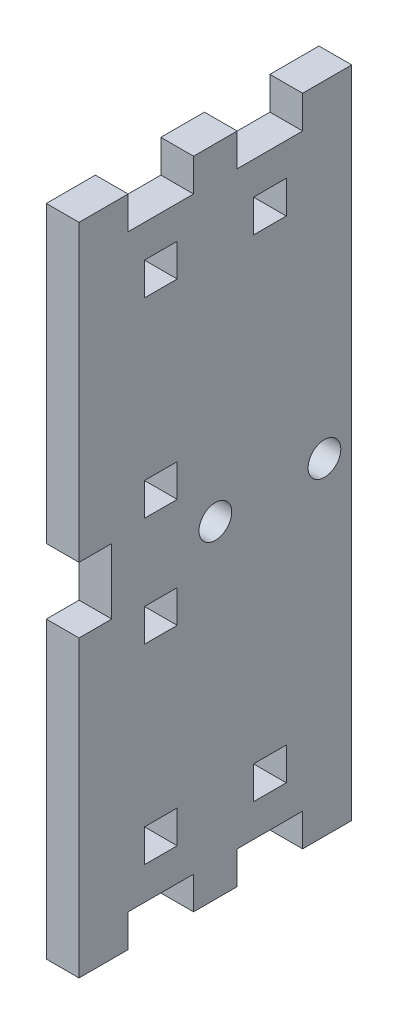
SolidWorks part; units mm, degrees
ref_plane "Front Plane" through (0, 0, 0) normal (0, 0, 1) x (1, 0, 0)
ref_plane "Top Plane" through (0, 0, 0) normal (0, 1, 0) x (1, 0, 0)
ref_plane "Right Plane" through (0, 0, 0) normal (1, 0, 0) x (0, 0, -1)
sketch "Sketch1" plane through (0, 0, 0) normal (1, 0, 0) x (0, 0, -1)
  line L0 (8, 30) -> (12.5, 30)
  line L1 (-12.5, 30) -> (-8, 30)
  line L2 (-12.5, 30) -> (-12.5, -30)
  line L3 (-12.5, -30) -> (-8, -30)
  line L4 (12.5, 30) -> (12.5, -30)
  line L7 (-8, 30) -> (-8, 27)
  line L8 (-2, 30) -> (-2, 27)
  line L9 (-8, 27) -> (-2, 27)
  line L10 (-2, -30) -> (2, -30)
  line L11 (2, 30) -> (2, 27)
  line L12 (8, 30) -> (8, 27)
  line L13 (2, 27) -> (8, 27)
  line L14 (-2, 30) -> (2, 30)
  line L16 (-8, -30) -> (-8, -27)
  line L17 (2, -27) -> (8, -27)
  line L18 (8, -27) -> (8, -30)
  line L19 (2, -30) -> (2, -27)
  line L20 (-8, -27) -> (-2, -27)
  line L21 (-2, -30) -> (-2, -27)
  line L22 (8, -30) -> (12.5, -30)
  point P0 (0, 0)
  point P6 (5, 27)
  point P15 (-5, 27)
  dimension "D1" = 25
  dimension "D2" = 60
  dimension "D3" = 6
  dimension "D4" = 6
  dimension "D5" = 3
  dimension "D6" = 3
  dimension "D7" = 7.5
  dimension "D8" = 7.5
extrude "Boss-Extrude1" add sketch "Sketch1" along normal blind 3
sketch "Sketch2" plane through (3, 0, 0) normal (1, 0, 0) x (0, 0, -1)
  line L0 (-18.5174, 0) -> (21.8209, 0) construction
  line L1 (-21.3613, 24) -> (23.7629, 24) construction
  line L2 (-2, 27) -> (-8, 27) construction
  line L3 (-6.5, 24) -> (-3.5, 24)
  line L4 (-6.5, 24) -> (-6.5, 21)
  line L5 (-3.5, 24) -> (-3.5, 21)
  line L6 (-6.5, 21) -> (-3.5, 21)
  line L7 (3.5, 24) -> (6.5, 24)
  line L8 (3.5, 24) -> (3.5, 21)
  line L9 (6.5, 24) -> (6.5, 21)
  line L10 (3.5, 21) -> (6.5, 21)
  line L11 (-12.5, 30) -> (-12.5, -30) construction
  line L12 (12.5, -30) -> (12.5, 30) construction
  line L13 (3.5, -21) -> (6.5, -21)
  line L14 (6.5, -24) -> (6.5, -21)
  line L15 (3.5, -24) -> (3.5, -21)
  line L16 (3.5, -24) -> (6.5, -24)
  line L17 (-6.5, -21) -> (-3.5, -21)
  line L18 (-3.5, -24) -> (-3.5, -21)
  line L19 (-6.5, -24) -> (-6.5, -21)
  line L20 (-6.5, -24) -> (-3.5, -24)
  point P16 (-5, 21)
  point P17 (5, 21)
  dimension "D1" = 3
  dimension "D2" = 3
  dimension "D3" = 3
  dimension "D4" = 3
  dimension "D5" = 3
  dimension "D6" = 7.5
  dimension "D7" = 7.5
extrude "Cut-Extrude1" cut sketch "Sketch2" against normal blind 3
sketch "Sketch3" plane through (3, 0, 0) normal (1, 0, 0) x (0, 0, -1)
  line L0 (-17.2913, 0) -> (34.7645, 0) construction
  circle A0 centre (0, 0) radius 1.5
  circle A1 centre (10, 0) radius 1.5
  dimension "D1" = 3
  dimension "D2" = 3
  dimension "D3" = 10
extrude "Cut-Extrude2" cut sketch "Sketch3" against normal blind 3
sketch "Sketch4" plane through (3, 0, 0) normal (1, 0, 0) x (0, 0, -1)
  line L0 (-18.3572, 0) -> (17.3444, 0) construction
  line L1 (-12.5, -3) -> (-12.5, 3)
  line L2 (-12.5, -3) -> (-9.5, -3)
  line L3 (-12.5, 3) -> (-9.5, 3)
  line L4 (-9.5, -3) -> (-9.5, 3)
  line L5 (-12.5, 30) -> (-12.5, -30) construction
  line L6 (-6.5, 10.0063) -> (-6.5, -10.1724) construction
  line L7 (-6.5, 3.5) -> (-6.5, 6.5)
  line L8 (-6.5, 3.5) -> (-3.5, 3.5)
  line L9 (-6.5, 6.5) -> (-3.5, 6.5)
  line L10 (-3.5, 3.5) -> (-3.5, 6.5)
  line L11 (-6.5, -3.5) -> (-6.5, -6.5)
  line L12 (-6.5, -3.5) -> (-3.5, -3.5)
  line L13 (-6.5, -6.5) -> (-3.5, -6.5)
  line L14 (-3.5, -3.5) -> (-3.5, -6.5)
  point P11 (-6.5, 5)
  point P20 (-6.5, -5)
  dimension "D1" = 6
  dimension "D2" = 3
  dimension "D3" = 3
  dimension "D4" = 6
  dimension "D5" = 3
  dimension "D6" = 3
  dimension "D7" = 3
  dimension "D8" = 3
  dimension "D9" = 5
  dimension "D10" = 5
extrude "Cut-Extrude3" cut sketch "Sketch4" against normal blind 10
